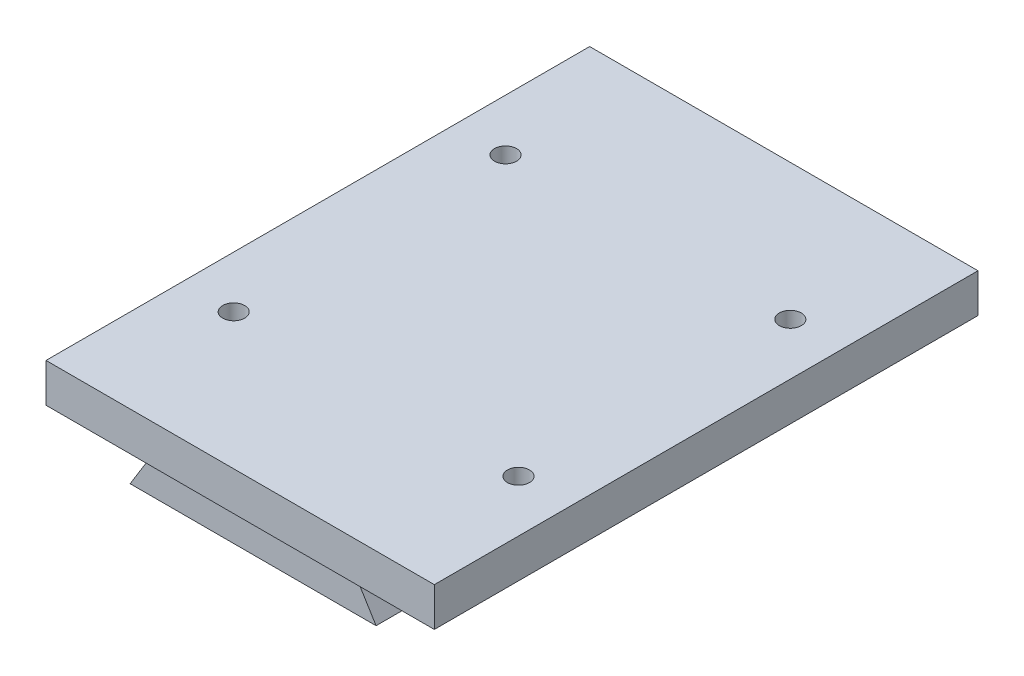
SolidWorks part; units mm, degrees
ref_plane "Front Plane" through (0, 0, 0) normal (0, 0, 1) x (1, 0, 0)
ref_plane "Top Plane" through (0, 0, 0) normal (0, 1, 0) x (1, 0, 0)
ref_plane "Right Plane" through (0, 0, 0) normal (1, 0, 0) x (0, 0, -1)
ref_plane "PZm34_4" through (0, -34.4, 0) normal (0, 1, 0) x (1, 0, 0)
sketch "Sketch1" plane through (0, -34.4, 0) normal (0, 1, 0) x (1, 0, 0)
  line L0 (-30, -112) -> (30, -112)
  line L1 (30, -112) -> (30, -28)
  line L2 (30, -28) -> (-30, -28)
  line L3 (-30, -28) -> (-30, -112)
extrude "Rail Plate" add sketch "Sketch1" along normal blind 6
ref_plane "PY30" through (0, 0, 30) normal (0, 0, 1) x (1, 0, 0)
sketch "Sketch2" plane through (0, 0, 30) normal (0, 0, 1) x (1, 0, 0)
  line L0 (-15, -33.9) -> (15, -33.9)
  line L1 (15, -33.9) -> (19, -40.4)
  line L2 (19, -40.4) -> (-19, -40.4)
  line L3 (-19, -40.4) -> (-15, -33.9)
extrude "Dovetail Rail" add sketch "Sketch2" along normal blind 80
ref_plane "PZm34_9" through (0, -34.9, 0) normal (0, 1, 0) x (1, 0, 0)
sketch "Sketch3" plane through (0, -34.9, 0) normal (0, 1, 0) x (1, 0, 0)
  circle A0 centre (-22, -91) radius 1.7
  circle A1 centre (-22, -49) radius 1.7
  circle A2 centre (22, -91) radius 1.7
  circle A3 centre (22, -49) radius 1.7
extrude "M3 Holes" cut sketch "Sketch3" along normal blind 7
sketch "Sketch4" plane through (0, -34.9, 0) normal (0, 1, 0) x (1, 0, 0)
  circle A0 centre (-22, -91) radius 3
  circle A1 centre (-22, -49) radius 3
  circle A2 centre (22, -91) radius 3
  circle A3 centre (22, -49) radius 3
extrude "Counterbores" cut sketch "Sketch4" along normal blind 4
equation "\"PlateX\" = 60.0"
equation "\"PlateY\" = 84.0"
equation "\"PlateT\" = 6.0"
equation "\"RailW\" = 30.0"
equation "\"RailW2\" = 38.0"
equation "\"RailH\" = 6.0"
equation "\"RailL\" = 80.0"
